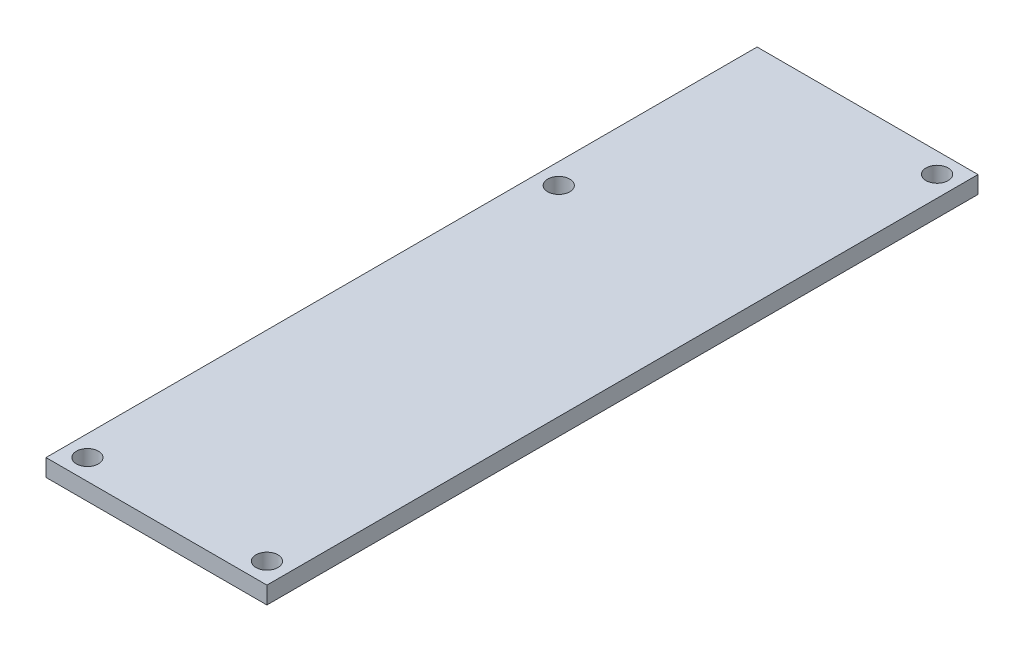
SolidWorks part; units mm, degrees
ref_plane "前视基准面" through (0, 0, 0) normal (0, 0, 1) x (1, 0, 0)
ref_plane "上视基准面" through (0, 0, 0) normal (0, 1, 0) x (1, 0, 0)
ref_plane "右视基准面" through (0, 0, 0) normal (1, 0, 0) x (0, 0, -1)
other "Configuration Table"
sketch "草图1" plane through (0, 0, 0) normal (0, 1, 0) x (1, 0, 0)
  line L0 (16, 103) -> (16, 0) construction
  line L1 (0, 0) -> (32, 0)
  line L2 (0, 0) -> (0, 103)
  line L3 (0, 103) -> (32, 103)
  line L4 (32, 0) -> (32, 103)
  line L5 (3, 3) -> (29, 3) construction
  line L6 (3, 3) -> (3, 71.27) construction
  line L7 (29, 3) -> (29, 100.07) construction
  circle A0 centre (3, 3) radius 1.6
  circle A1 centre (29, 3) radius 1.6
  circle A2 centre (3, 71.27) radius 1.6
  circle A3 centre (29, 100.07) radius 1.6
  dimension "D5" = 3.2
  dimension "D6" = 3.2
  dimension "D7" = 68.27
  dimension "D9" = 3.2
  dimension "D1" = 32
  dimension "D2" = 103
  dimension "D3" = 26
  dimension "D4" = 3
  dimension "D8" = 97.07
extrude "凸台-拉伸1" add sketch "草图1" along normal blind 2.5
